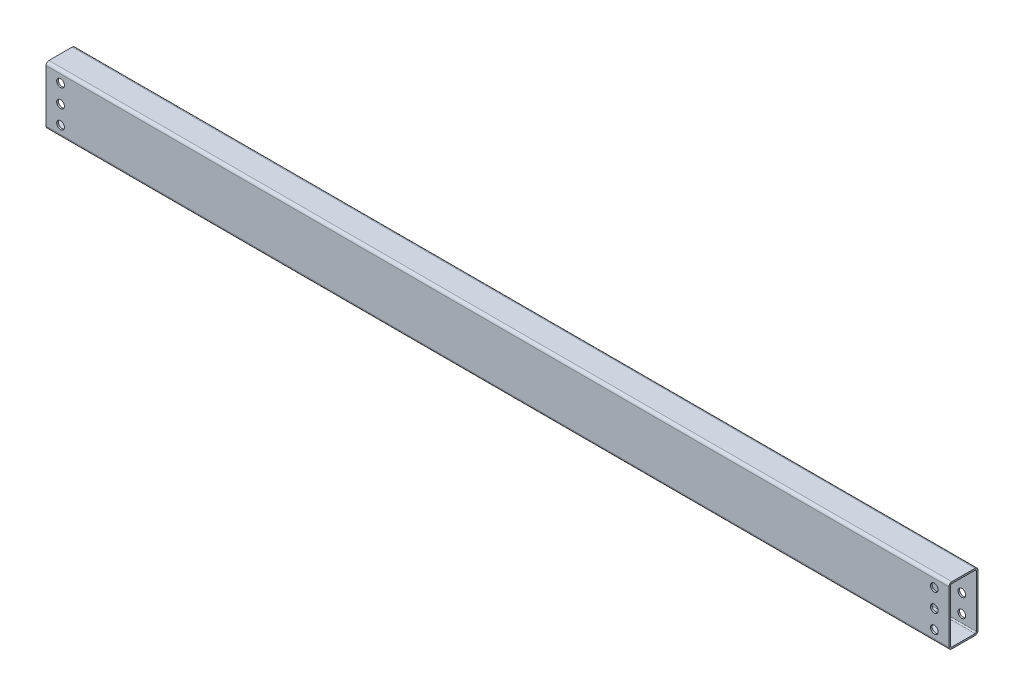
SolidWorks part; units mm, degrees
material "6061-T6 (SS)"
ref_plane "Front" through (0, 0, 0) normal (0, 0, 1) x (1, 0, 0)
ref_plane "Top" through (0, 0, 0) normal (0, 1, 0) x (1, 0, 0)
ref_plane "Right" through (0, 0, 0) normal (1, 0, 0) x (0, 0, -1)
sketch "Sketch1" plane through (0, 0, 0) normal (1, 0, 0) x (0, 0, -1)
  line L0 (10.16, -25.4) -> (-10.16, -25.4)
  line L1 (12.7, -22.86) -> (12.7, 22.86)
  line L2 (10.16, 25.4) -> (-10.16, 25.4)
  line L3 (-12.7, -22.86) -> (-12.7, 22.86)
  line L4 (12.7, -25.4) -> (-12.7, 25.4) construction
  line L5 (12.7, 25.4) -> (-12.7, -25.4) construction
  arc A0 (-10.16, -25.4) -> (-12.7, -22.86) centre (-10.16, -22.86) cw
  arc A1 (10.16, -25.4) -> (12.7, -22.86) centre (10.16, -22.86) ccw
  arc A2 (12.7, 22.86) -> (10.16, 25.4) centre (10.16, 22.86) ccw
  arc A3 (-10.16, 25.4) -> (-12.7, 22.86) centre (-10.16, 22.86) ccw
  point P0 (0, 0)
  dimension "D3" = 2.54
  dimension "D1" = 25.4
  dimension "D2" = 50.8
extrude "Extrude-Thin1" add sketch "Sketch1" along normal mid plane 787.4 thin
hole_wizard "1/4 Clearance Hole1" positions "Sketch2" profile "Sketch3" hole size "1/4" standard "ANSI Inch" end condition through all
sketch "Sketch2" plane through (0, 0, -12.7) normal (0, 0, -1) x (-1, 0, 0)
  line L0 (-393.7, -22.86) -> (-393.7, 22.86) construction
  line L1 (-393.7, 25.4) -> (393.7, 25.4) construction
  line L2 (-393.7, -25.4) -> (393.7, -25.4) construction
  line L3 (-381, 15.875) -> (-381, -15.875) construction
  line L4 (0, 0) -> (0, -37.3791) construction
  point P0 (-381, 15.875)
  point P2 (-381, -15.875)
  point P15 (-381, 0)
  point P23 (381, -15.875)
  point P24 (381, 0)
  point P25 (381, 15.875)
  dimension "D1" = 12.7
  dimension "D2" = 9.525
  dimension "D3" = 9.525
sketch "Sketch3" plane through (381, 15.875, -12.7) normal (1, 0, 0) x (0, 1, 0)
  line L0 (0, 0) -> (0, 25.4)
  line L1 (0, 25.4) -> (3.3782, 25.4)
  line L2 (3.3782, 25.4) -> (3.3782, 0)
  line L5 (3.3782, 0) -> (0, 0)
  line L11 (0, -6.35) -> (0, 107.95) construction
  dimension "Thru Hole Dia." = 6.7564
  dimension "Thru Hole Depth" = 25.4
hole_wizard "1/4 Clearance Hole2" positions "Sketch4" profile "Sketch5" hole size "1/4" standard "ANSI Inch"
sketch "Sketch4" plane through (0, 0, -12.7) normal (0, 0, -1) x (-1, 0, 0)
  line L0 (-234.95, 15.875) -> (-234.95, -15.875) construction
  line L2 (-393.7, 25.4) -> (393.7, 25.4) construction
  line L3 (-393.7, -25.4) -> (393.7, -25.4) construction
  line L4 (0, 0) -> (0, -51.4899) construction
  point P19 (-234.95, 15.875)
  point P21 (-234.95, 0)
  point P23 (-234.95, -15.875)
  point P42 (234.95, -15.875)
  point P43 (234.95, 0)
  point P44 (234.95, 15.875)
  dimension "D1" = 9.525
  dimension "D2" = 9.525
  dimension "D3" = 469.9
sketch "Sketch5" plane through (234.95, 15.875, -12.7) normal (1, 0, 0) x (0, 1, 0)
  line L0 (0, 0) -> (0, 1.4478)
  line L1 (0, 1.4478) -> (3.3782, 1.4478)
  line L2 (3.3782, 1.4478) -> (3.3782, 0)
  line L5 (3.3782, 0) -> (0, 0)
  line L11 (0, -6.35) -> (0, 107.95) construction
  dimension "Thru Hole Dia." = 6.7564
  dimension "Thru Hole Depth" = 1.4478
sketch "Sketch6" plane through (0, 0, -12.7) normal (0, 0, -1) x (-1, 0, 0)
  line L0 (-393.7, -25.4) -> (393.7, -25.4) construction
  line L2 (-120.65, -25.4) -> (-107.95, -25.4)
  line L3 (-120.65, -25.4) -> (-120.65, 15.875)
  line L4 (-117.475, 19.05) -> (-111.125, 19.05)
  line L5 (-107.95, -25.4) -> (-107.95, 15.875)
  line L6 (-44.45, -25.4) -> (-31.75, -25.4)
  line L11 (-44.45, -25.4) -> (-44.45, 15.875)
  line L12 (-41.275, 19.05) -> (-34.925, 19.05)
  line L13 (-31.75, -25.4) -> (-31.75, 15.875)
  line L14 (31.75, -25.4) -> (44.45, -25.4)
  line L15 (31.75, -25.4) -> (31.75, 15.875)
  line L16 (34.925, 19.05) -> (41.275, 19.05)
  line L17 (44.45, -25.4) -> (44.45, 15.875)
  line L18 (107.95, -25.4) -> (120.65, -25.4)
  line L19 (107.95, -25.4) -> (107.95, 15.875)
  line L20 (111.125, 19.05) -> (117.475, 19.05)
  line L21 (120.65, -25.4) -> (120.65, 15.875)
  line L22 (0, 0) -> (0, -9.525) construction
  arc A0 (-111.125, 19.05) -> (-107.95, 15.875) centre (-111.125, 15.875) cw
  arc A1 (-120.65, 15.875) -> (-117.475, 19.05) centre (-117.475, 15.875) cw
  arc A4 (-34.925, 19.05) -> (-31.75, 15.875) centre (-34.925, 15.875) cw
  arc A5 (-44.45, 15.875) -> (-41.275, 19.05) centre (-41.275, 15.875) cw
  arc A6 (41.275, 19.05) -> (44.45, 15.875) centre (41.275, 15.875) cw
  arc A7 (31.75, 15.875) -> (34.925, 19.05) centre (34.925, 15.875) cw
  arc A8 (117.475, 19.05) -> (120.65, 15.875) centre (117.475, 15.875) cw
  arc A9 (107.95, 15.875) -> (111.125, 19.05) centre (111.125, 15.875) cw
  dimension "D1" = 3.175
  dimension "D2" = 12.7
  dimension "D3" = 44.45
  dimension "D5" = 76.2
  dimension "D4" = 4
extrude "Cut-Extrude1" cut sketch "Sketch6" against normal blind 9.525
